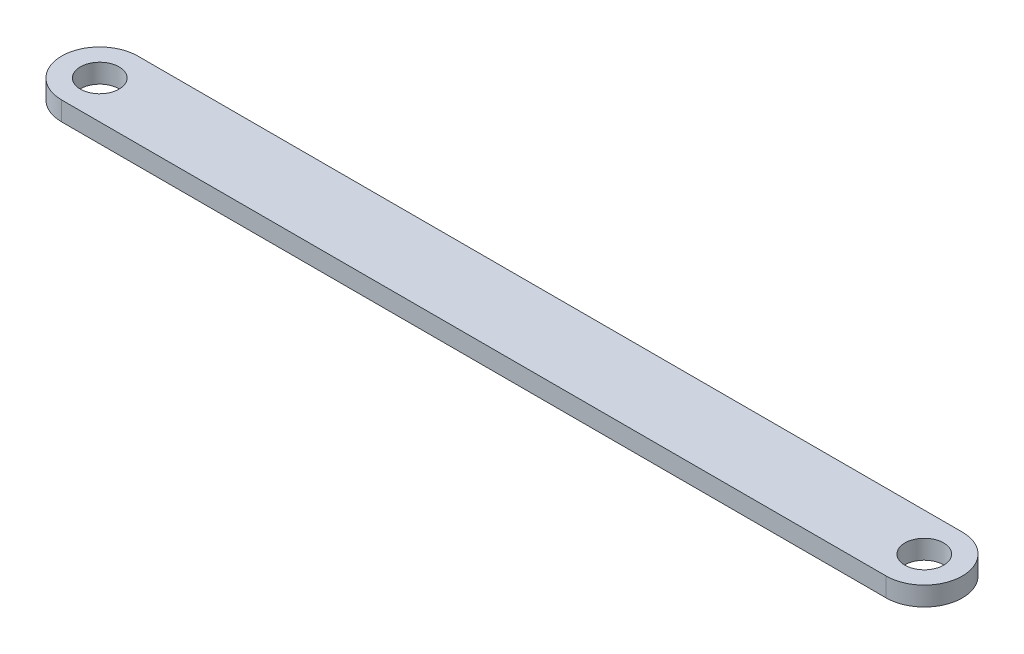
SolidWorks part; units mm, degrees
material "ABS"
ref_plane "Front Plane" through (0, 0, 0) normal (0, 0, 1) x (1, 0, 0)
ref_plane "Top Plane" through (0, 0, 0) normal (0, 1, 0) x (1, 0, 0)
ref_plane "Right Plane" through (0, 0, 0) normal (1, 0, 0) x (0, 0, -1)
sketch "Sketch1" plane through (0, 0, 0) normal (0, 1, 0) x (1, 0, 0)
  line L0 (0, 0) -> (130, 0) construction
  line L1 (-55, 0) -> (55, 0) construction
  line L2 (0, 6) -> (130, 6)
  line L3 (0, -6) -> (130, -6)
  arc A0 (0, 6) -> (0, -6) centre (0, 0) ccw
  arc A1 (130, -6) -> (130, 6) centre (130, 0) ccw
  circle A2 centre (0, 0) radius 3.05
  circle A3 centre (130, 0) radius 3.05
  point P5 (65, 0)
  dimension "D3" = 6.1
  dimension "D1" = 130
  dimension "D2" = 12
extrude "Boss-Extrude1" add sketch "Sketch1" along normal blind 3
